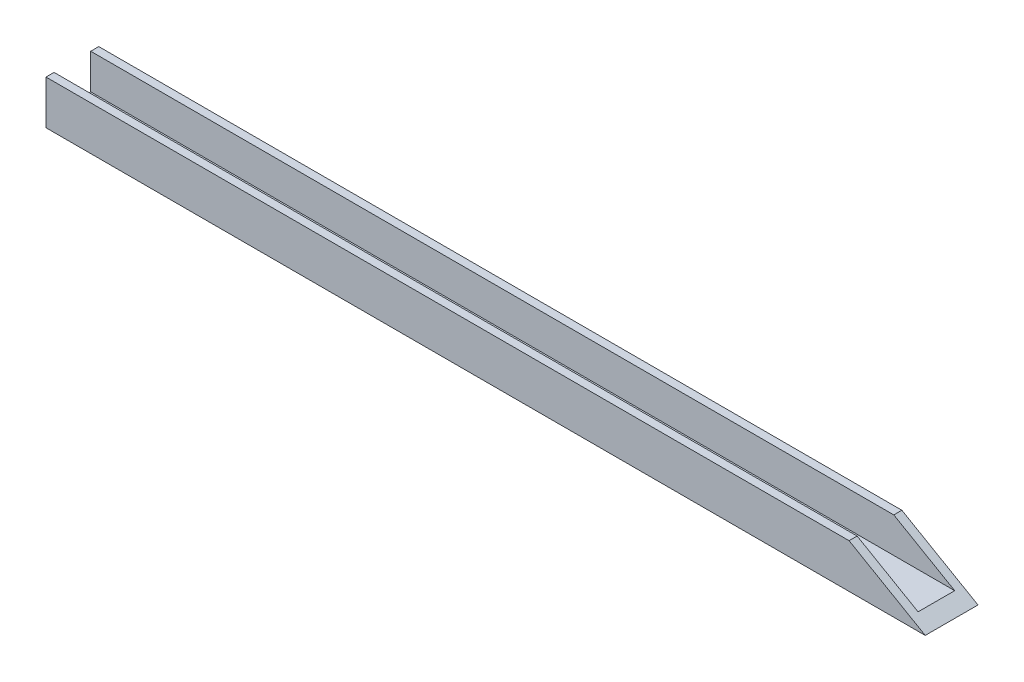
SolidWorks part; units mm, degrees
ref_plane "Front Plane" through (0, 0, 0) normal (0, 0, 1) x (1, 0, 0)
ref_plane "Top Plane" through (0, 0, 0) normal (0, 1, 0) x (1, 0, 0)
ref_plane "Right Plane" through (0, 0, 0) normal (1, 0, 0) x (0, 0, -1)
sketch "Sketch1" plane through (0, 0, 0) normal (0, 1, 0) x (1, 0, 0)
  line L1 (-50, 3) -> (50, 3)
  line L2 (-50, 3) -> (-50, -3)
  line L3 (-50, -3) -> (50, -3)
  line L4 (50, 3) -> (50, -3)
  line L5 (-50, 3) -> (50, -3) construction
  line L6 (-50, -3) -> (50, 3) construction
  point P0 (0, 0)
  dimension "D1" = 6
  dimension "D2" = 100
extrude "Boss-Extrude1" add sketch "Sketch1" along normal blind 5
sketch "Sketch2" plane through (0, 5, 0) normal (0, 1, 0) x (1, 0, 0)
  line L0 (50, -3) -> (50, 3) construction
  line L1 (-50, 2.0838) -> (50, 2.0838)
  line L2 (-50, 2.0838) -> (-50, -2.0837)
  line L3 (-50, -2.0837) -> (50, -2.0837)
  line L4 (50, 2.0838) -> (50, -2.0837)
  line L5 (-50, 2.0838) -> (50, -2.0837) construction
  line L6 (-50, -2.0837) -> (50, 2.0838) construction
  point P0 (0, 0)
  dimension "D1" = 4.1675
extrude "Cut-Extrude1" cut sketch "Sketch2" against normal blind 4
sketch "Sketch3" plane through (0, 0, 3) normal (0, 0, 1) x (1, 0, 0)
  line L0 (50, 0) -> (41.3397, 5)
  line L1 (-50, 5) -> (50, 5) construction
  line L2 (41.3397, 5) -> (50, 5)
  line L3 (50, 5) -> (50, 0)
  dimension "D1" = 10
extrude "Cut-Extrude2" cut sketch "Sketch3" against normal blind 20
